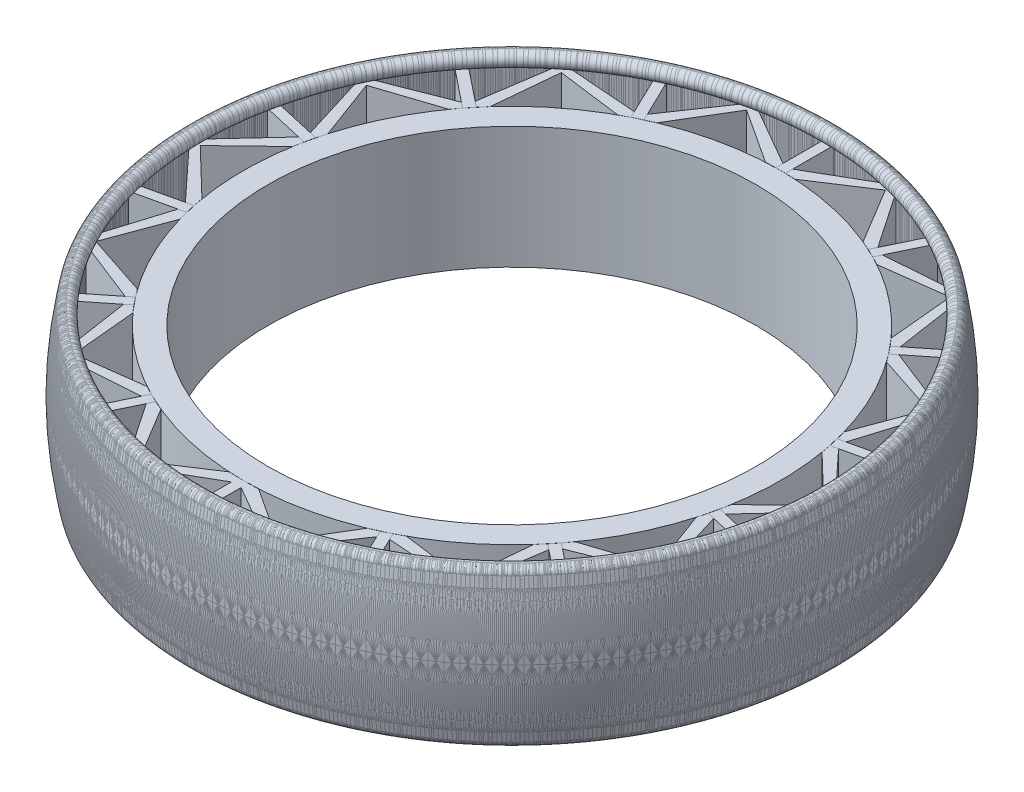
SolidWorks part; units mm, degrees
ref_plane "Спереди" through (0, 0, 0) normal (0, 0, 1) x (1, 0, 0)
ref_plane "Сверху" through (0, 0, 0) normal (0, 1, 0) x (1, 0, 0)
ref_plane "Справа" through (0, 0, 0) normal (1, 0, 0) x (0, 0, -1)
sketch "Эскиз1" plane through (0, 0, 0) normal (0, 1, 0) x (1, 0, 0)
  circle A0 centre (0, 0) radius 100
  circle A1 centre (0, 0) radius 110
  dimension "D1" = 220
  dimension "D2" = 200
extrude "Бобышка-Вытянуть1" add sketch "Эскиз1" along normal blind 50
sketch "Эскиз3" plane through (0, 0, 0) normal (0, -1, 0) x (-1, 0, 0)
  circle A0 centre (0, 0) radius 130
  circle A1 centre (0, 0) radius 135
  dimension "D1" = 270
  dimension "D2" = 260
sketch "Эскиз2" plane through (0, 0, 0) normal (0, -1, 0) x (1, 0, 0)
  line L0 (0, 0) -> (0, 130) construction
  line L3 (-2, 109.9818) -> (-2, 129.9846)
  line L4 (2, 109.9818) -> (2, 129.9846)
  circle A0 centre (0, 0) radius 110 construction
  arc A1 (-2, 109.9818) -> (0, 110) centre (-0.5, 55) cw
  circle A2 centre (0, 0) radius 100 construction
  arc A4 (-2, 129.9846) -> (2, 129.9846) centre (0, 0) cw
  arc A5 (2, 109.9818) -> (0, 110) centre (0.5, 55) ccw
  point P9 (0, 0)
  point P10 (0, 0)
  dimension "D1" = 4
  dimension "D2" = 20
extrude "Бобышка-Вытянуть2" add sketch "Эскиз2" against normal blind 50 separate body
sketch "Эскиз5" plane through (0, 0, 0) normal (1, 0, 0) x (0, 0, -1)
  line L0 (-129.9846, 0) -> (-129.9846, 50)
  line L1 (-131.9846, 54.5207) -> (-132.7071, 50.4234)
  line L2 (-156.6734, 25) -> (-138.2129, 25) construction
  line L3 (-131.9846, 54.5207) -> (-131.9846, 45.2701) construction
  line L4 (-129.9846, 50) -> (-129.9846, 0)
  line L5 (-129.9846, 25) -> (-129.9846, 50)
  line L6 (-131.9846, -4.5207) -> (-132.7071, -0.4234)
  line L7 (-129.9846, 0) -> (-129.9846, 50)
  line L8 (0, 0) -> (0, 64.3857) construction
  arc A0 (-129.9846, 50) -> (-128.996, 50.9999) centre (-128.9846, 50) cw
  arc A1 (-128.996, 50.9999) -> (-131.9846, 54.5207) centre (-129.0302, 53.9997) ccw
  arc A3 (-132.7071, 50.4234) -> (-134.9846, 25) centre (15.0141, 24.3762) ccw
  arc A6 (-129.9846, 0) -> (-128.996, -0.9999) centre (-128.9846, 0) ccw
  arc A7 (-128.996, -0.9999) -> (-131.9846, -4.5207) centre (-129.0302, -3.9997) cw
  arc A8 (-132.7071, -0.4234) -> (-134.9846, 25) centre (15.0141, 25.6238) cw
  point P13 (-129.9846, 25)
  dimension "D2" = 1
  dimension "D3" = 3
  dimension "D1" = 150
  dimension "D4" = 10
  dimension "D5" = 2
  dimension "D6" = 5
revolve "Повернуть2" add sketch "Эскиз5" angle 360 about L8
sketch "Эскиз4" plane through (0, 0, 0) normal (0, -1, 0) x (1, 0, 0)
  line L1 (-31.0603, 126.2349) -> (-6, 109.8362)
  line L2 (-2, 109.9818) -> (7.953, 109.9818) construction
  line L3 (-2, 109.9818) -> (-2, 112.9818)
  line L4 (-2, 129.9692) -> (-2, 109.9818) construction
  line L5 (-2, 112.9818) -> (-26.6825, 127.2323)
  line L6 (0, 148.9306) -> (0, 117.9564) construction
  line L7 (31.0603, 126.2349) -> (6, 109.8362)
  line L8 (2, 112.9818) -> (26.6825, 127.2323)
  line L9 (2, 109.9818) -> (2, 112.9818)
  circle A0 centre (0, 0) radius 130 construction
  arc A1 (-26.6825, 127.2323) -> (-31.0603, 126.2349) centre (0, 0) ccw
  circle A2 centre (0, 0) radius 110 construction
  arc A3 (-6, 109.8362) -> (-2, 109.9818) centre (0, 0) cw
  arc A4 (6, 109.8362) -> (2, 109.9818) centre (0, 0) ccw
  arc A5 (26.6825, 127.2323) -> (31.0603, 126.2349) centre (0, 0) cw
  point P3 (0, 0)
  point P13 (0, 0)
  dimension "D1" = 4
  dimension "D2" = 31.0603
  dimension "D3" = 3
  dimension "D4" = 150
pattern_circular "Круговой массив17" count 14 over 360 about axis through (0, 0, 0) along (0, 1, 0) of bodies 111
extrude "Бобышка-Вытянуть5" add sketch "Эскиз4" against normal up to surface (50 mm away) up to face at (0, 50, 117.9871)
pattern_circular "Круговой массив18" count 14 over 360 about axis through (0, 0, 0) along (0, 1, 0) of "Бобышка-Вытянуть5"
